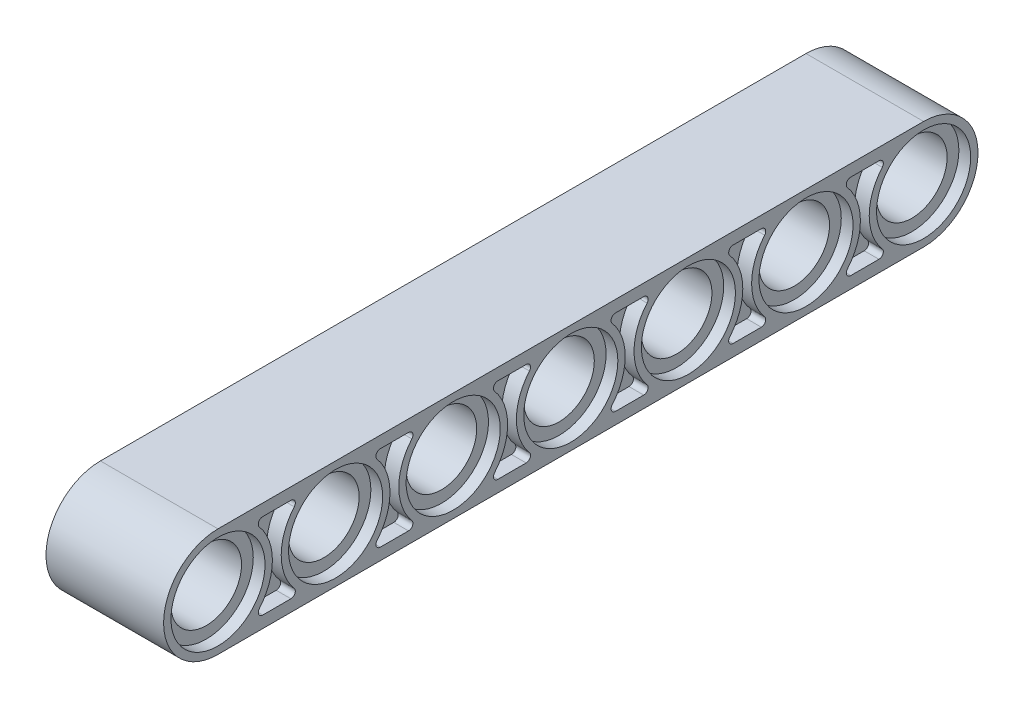
SolidWorks part; units mm, degrees
ref_plane "Front Plane" through (0, 0, 0) normal (0, 0, 1) x (1, 0, 0)
ref_plane "Top Plane" through (0, 0, 0) normal (0, 1, 0) x (1, 0, 0)
ref_plane "Right Plane" through (0, 0, 0) normal (1, 0, 0) x (0, 0, -1)
sketch "Sketch1" plane through (0, 0, 0) normal (1, 0, 0) x (0, 0, -1)
  line L0 (-10.6497, 0) -> (37.3503, 0) construction
  line L1 (-10.6497, 3.7) -> (37.3503, 3.7)
  line L2 (-10.6497, -3.7) -> (37.3503, -3.7)
  arc A0 (-10.6497, 3.7) -> (-10.6497, -3.7) centre (-10.6497, 0) ccw
  arc A1 (37.3503, -3.7) -> (37.3503, 3.7) centre (37.3503, 0) ccw
  circle A2 centre (-10.6497, 0) radius 2.4
  circle A3 centre (-2.6497, 0) radius 2.4
  circle A4 centre (5.3503, 0) radius 2.4
  circle A5 centre (13.3503, 0) radius 2.4
  circle A6 centre (21.3503, 0) radius 2.4
  circle A7 centre (29.3503, 0) radius 2.4
  circle A8 centre (37.3503, 0) radius 2.4
  point P3 (13.3503, 0)
  dimension "D3" = 7
  dimension "D1" = 7.4
  dimension "D2" = 48
extrude "Boss-Extrude1" add sketch "Sketch1" along normal blind 8
sketch "Sketch2" plane through (8, 0, 0) normal (1, 0, 0) x (0, 0, -1)
  circle A0 centre (-10.6497, 0) radius 3.2
  circle A1 centre (-2.6497, 0) radius 3.2
  circle A2 centre (5.3503, 0) radius 3.2
  circle A3 centre (13.3503, 0) radius 3.2
  circle A4 centre (21.3503, 0) radius 3.2
  circle A5 centre (29.3503, 0) radius 3.2
  circle A6 centre (37.3503, 0) radius 3.2
  dimension "D1" = 7
extrude "Cut-Extrude1" cut sketch "Sketch2" against normal blind 0.8
sketch "Sketch3" plane through (8, 0, 0) normal (1, 0, 0) x (0, 0, -1)
  line L0 (-7.61, 2.9) -> (-5.6895, 2.9)
  line L1 (37.3503, 3.7) -> (-10.6497, 3.7) construction
  line L2 (-10.6497, 0) -> (-16.1817, 0) construction
  line L3 (-7.61, -2.9) -> (-5.6895, -2.9)
  line L4 (0.39, 2.9) -> (2.3105, 2.9)
  line L5 (0.39, -2.9) -> (2.3105, -2.9)
  line L6 (8.39, 2.9) -> (10.3105, 2.9)
  line L7 (8.39, -2.9) -> (10.3105, -2.9)
  line L8 (16.39, 2.9) -> (18.3105, 2.9)
  line L9 (16.39, -2.9) -> (18.3105, -2.9)
  line L10 (24.39, 2.9) -> (26.3105, 2.9)
  line L11 (24.39, -2.9) -> (26.3105, -2.9)
  line L12 (32.39, 2.9) -> (34.3105, 2.9)
  line L13 (32.39, -2.9) -> (34.3105, -2.9)
  arc A0 (-7.838, -2.405) -> (-7.838, 2.405) centre (-10.6497, 0) ccw
  arc A1 (-5.4615, 2.405) -> (-5.4615, -2.405) centre (-2.6497, 0) ccw
  arc A2 (-7.838, -2.405) -> (-7.61, -2.9) centre (-7.61, -2.6) ccw
  arc A3 (-5.4615, -2.405) -> (-5.6895, -2.9) centre (-5.6895, -2.6) cw
  arc A4 (-5.6895, 2.9) -> (-5.4615, 2.405) centre (-5.6895, 2.6) cw
  arc A5 (-7.838, 2.405) -> (-7.61, 2.9) centre (-7.61, 2.6) cw
  arc A6 (0.162, -2.405) -> (0.162, 2.405) centre (-2.6497, 0) ccw
  arc A7 (2.5385, 2.405) -> (2.5385, -2.405) centre (5.3503, 0) ccw
  arc A8 (0.162, -2.405) -> (0.39, -2.9) centre (0.39, -2.6) ccw
  arc A9 (2.5385, -2.405) -> (2.3105, -2.9) centre (2.3105, -2.6) cw
  arc A10 (2.3105, 2.9) -> (2.5385, 2.405) centre (2.3105, 2.6) cw
  arc A11 (0.162, 2.405) -> (0.39, 2.9) centre (0.39, 2.6) cw
  arc A12 (8.162, -2.405) -> (8.162, 2.405) centre (5.3503, 0) ccw
  arc A13 (10.5385, 2.405) -> (10.5385, -2.405) centre (13.3503, 0) ccw
  arc A14 (8.162, -2.405) -> (8.39, -2.9) centre (8.39, -2.6) ccw
  arc A15 (10.5385, -2.405) -> (10.3105, -2.9) centre (10.3105, -2.6) cw
  arc A16 (10.3105, 2.9) -> (10.5385, 2.405) centre (10.3105, 2.6) cw
  arc A17 (8.162, 2.405) -> (8.39, 2.9) centre (8.39, 2.6) cw
  arc A18 (16.162, -2.405) -> (16.162, 2.405) centre (13.3503, 0) ccw
  arc A19 (18.5385, 2.405) -> (18.5385, -2.405) centre (21.3503, 0) ccw
  arc A20 (16.162, -2.405) -> (16.39, -2.9) centre (16.39, -2.6) ccw
  arc A21 (18.5385, -2.405) -> (18.3105, -2.9) centre (18.3105, -2.6) cw
  arc A22 (18.3105, 2.9) -> (18.5385, 2.405) centre (18.3105, 2.6) cw
  arc A23 (16.162, 2.405) -> (16.39, 2.9) centre (16.39, 2.6) cw
  arc A24 (24.162, -2.405) -> (24.162, 2.405) centre (21.3503, 0) ccw
  arc A25 (26.5385, 2.405) -> (26.5385, -2.405) centre (29.3503, 0) ccw
  arc A26 (24.162, -2.405) -> (24.39, -2.9) centre (24.39, -2.6) ccw
  arc A27 (26.5385, -2.405) -> (26.3105, -2.9) centre (26.3105, -2.6) cw
  arc A28 (26.3105, 2.9) -> (26.5385, 2.405) centre (26.3105, 2.6) cw
  arc A29 (24.162, 2.405) -> (24.39, 2.9) centre (24.39, 2.6) cw
  arc A30 (32.162, -2.405) -> (32.162, 2.405) centre (29.3503, 0) ccw
  arc A31 (34.5385, 2.405) -> (34.5385, -2.405) centre (37.3503, 0) ccw
  arc A32 (32.162, -2.405) -> (32.39, -2.9) centre (32.39, -2.6) ccw
  arc A33 (34.5385, -2.405) -> (34.3105, -2.9) centre (34.3105, -2.6) cw
  arc A34 (34.3105, 2.9) -> (34.5385, 2.405) centre (34.3105, 2.6) cw
  arc A35 (32.162, 2.405) -> (32.39, 2.9) centre (32.39, 2.6) cw
  dimension "D1" = 2
  dimension "D3" = 0.3
  dimension "D2" = 0.8
  dimension "D4" = 6
extrude "Cut-Extrude2" cut sketch "Sketch3" against normal blind 1
ref_plane "Plane1" through (4, 0, 0) normal (1, 0, 0) x (0, 0, -1)
mirror "Mirror1" about plane through (4, 0, 0) normal (1, 0, 0) of "Cut-Extrude2", "Cut-Extrude1"
